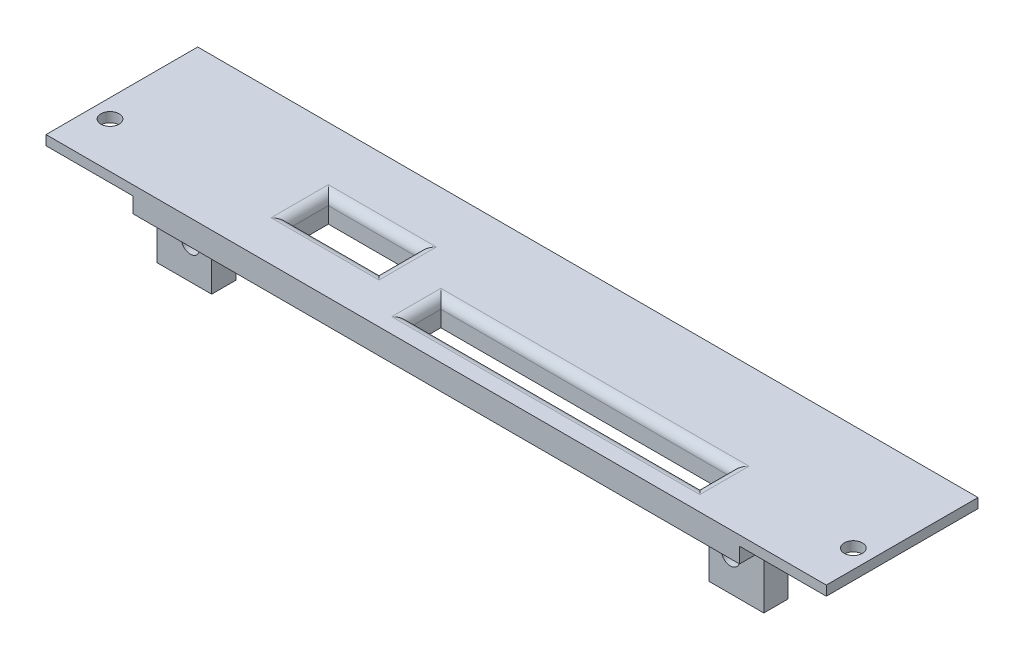
SolidWorks part; units mm, degrees
ref_plane "Front Plane" through (0, 0, 0) normal (0, 0, 1) x (1, 0, 0)
ref_plane "Top Plane" through (0, 0, 0) normal (0, 1, 0) x (1, 0, 0)
ref_plane "Right Plane" through (0, 0, 0) normal (1, 0, 0) x (0, 0, -1)
sketch "Sketch1" plane through (0, 0, 0) normal (0, 1, 0) x (1, 0, 0)
  line L5 (-64.3, 12.5) -> (64.3, 12.5)
  line L6 (-64.3, 12.5) -> (-64.3, -12.5)
  line L7 (-64.3, -12.5) -> (64.3, -12.5)
  line L8 (64.3, 12.5) -> (64.3, -12.5)
  circle A0 centre (-61.25, -5) radius 1.5
  circle A1 centre (61.25, -5) radius 1.5
  point P0 (0, 0)
  dimension "D1" = 128.6
  dimension "D2" = 25
  dimension "D5" = 7.5
  dimension "D6" = 7.5
extrude "Boss-Extrude1" add sketch "Sketch1" along normal blind 1.6
ref_plane "PCB_back" through (0, -2.54, 0) normal (0, 1, 0) x (1, 0, 0)
ref_plane "PCB_top" through (0, 0, 8.5) normal (0, 0, 1) x (1, 0, 0)
sketch "Sketch3" plane through (0, 0, 0) normal (0, 1, 0) x (1, 0, 0)
  line L0 (64.3, 12.5) -> (-64.3, 12.5) construction
  line L1 (-50, 12.5) -> (50, 12.5)
  line L2 (-50, 12.5) -> (-50, -12.5)
  line L3 (-50, -12.5) -> (50, -12.5)
  line L4 (50, 12.5) -> (50, -12.5)
  line L5 (-64.3, -12.5) -> (64.3, -12.5) construction
  dimension "D1" = 100
  dimension "D2" = 25
extrude "Boss-Extrude4" add sketch "Sketch3" against normal blind 2.54
sketch "Sketch4" plane through (0, 0, 8.5) normal (0, 0, 1) x (1, 0, 0)
  line L0 (-50, -2.54) -> (50, -2.54) construction
  line L1 (-50, -2.54) -> (-41, -2.54)
  line L2 (-50, -2.54) -> (-50, -11.54)
  line L3 (-50, -11.54) -> (-41, -11.54)
  line L4 (-41, -2.54) -> (-41, -11.54)
  line L5 (50, -2.54) -> (41, -2.54)
  line L6 (50, -2.54) -> (50, -11.54)
  line L7 (50, -11.54) -> (41, -11.54)
  line L8 (41, -2.54) -> (41, -11.54)
  line L9 (0, -55) -> (0, 55) construction
  circle A0 centre (44.5, -6.08) radius 1.5
  circle A1 centre (-44.5, -6.08) radius 1.5
  dimension "D1" = 9
  dimension "D2" = 9
  dimension "D3" = 9
  dimension "D4" = 9
  dimension "D5" = 0
  dimension "D6" = 0
  dimension "D7" = 82
  dimension "D8" = 50
  dimension "D9" = 5.5
  dimension "D10" = 3.54
  dimension "D11" = 5.5
  dimension "D12" = 3.54
extrude "Boss-Extrude5" add sketch "Sketch4" against normal blind 4
fillet "Fillet1" radius 2 2 edges at (-45.5, -2.54, 4.5) (45.5, -2.54, 4.5)
sketch "Sketch5" plane through (0, 1.6, 0) normal (0, 1, 0) x (1, 0, 0)
  line L0 (-8.3221, -8.5) -> (39.4564, -8.5)
  line L1 (-32.3812, 2.121) -> (-17.5956, 2.121)
  line L2 (-32.3812, 2.121) -> (-32.3812, -4.3304)
  line L3 (-32.3812, -4.3304) -> (-17.5956, -4.3304)
  line L4 (-17.5956, 2.121) -> (-17.5956, -4.3304)
  line L5 (-8.3221, -3.4046) -> (39.4564, -3.4046)
  line L6 (-8.3221, -3.4046) -> (-8.3221, -8.5)
  line L8 (39.4564, -3.4046) -> (39.4564, -8.5)
  point P12 (0, 0)
  point P13 (0, 0)
  point P14 (0, 0)
  point P15 (0, 0)
  point P16 (0, 0)
  point P17 (0, 0)
  point P18 (0, 0)
  point P19 (0, 0)
extrude "Cut-Extrude1" cut sketch "Sketch5" against normal through all
fillet "Fillet2" radius 1.5 8 edges at (-24.9884, 1.6, 4.3304) (-32.3812, 1.6, 1.1047) (-24.9884, 1.6, -2.121) (-17.5956, 1.6, 1.1047) (39.4564, 1.6, 5.9523) (15.5672, 1.6, 8.5) (-8.3221, 1.6, 5.9523) (15.5672, 1.6, 3.4046)
equation "\"D10@Sketch4\"=\"D12@Sketch4\""
equation "\"D9@Sketch4\"=\"D11@Sketch4\""
equation "\"D3@Sketch4\"=\"D2@Sketch4\""
